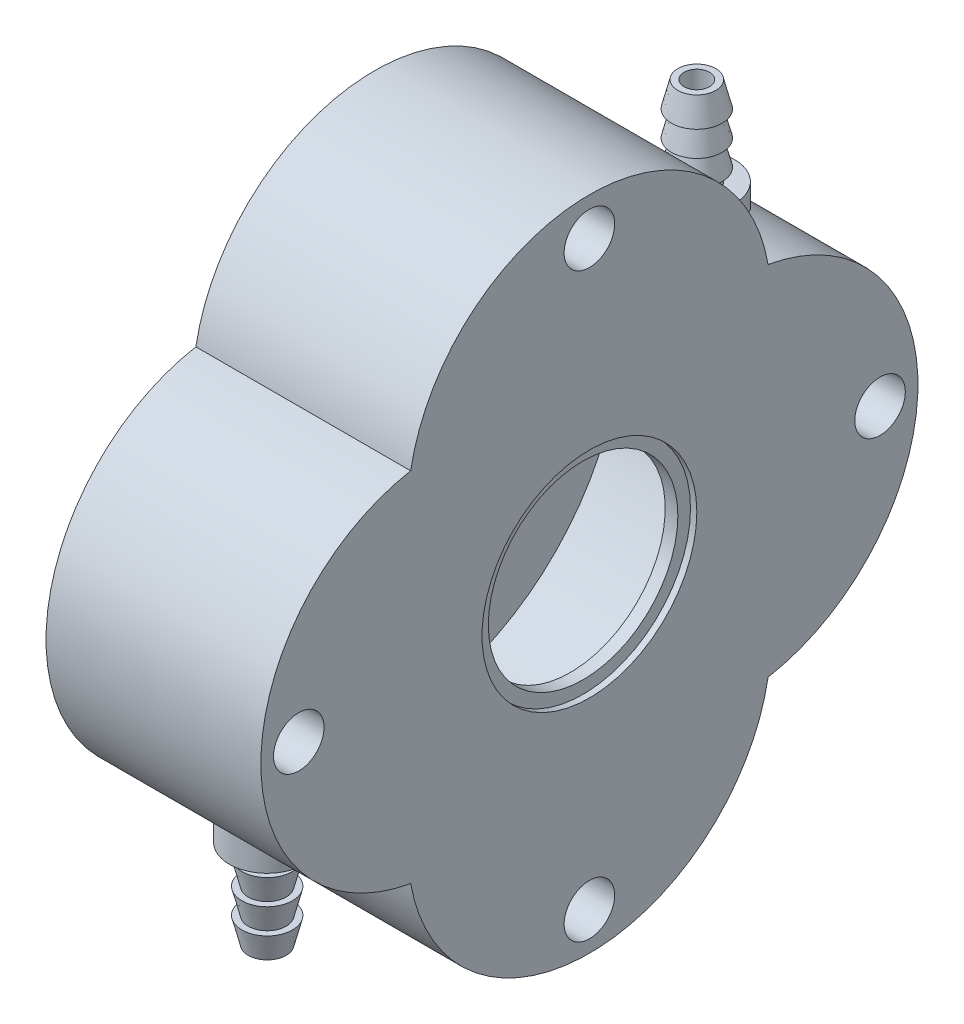
SolidWorks part; units mm, degrees
ref_plane "Front Plane" through (0, 0, 0) normal (0, 0, 1) x (1, 0, 0)
ref_plane "Top Plane" through (0, 0, 0) normal (0, 1, 0) x (1, 0, 0)
ref_plane "Right Plane" through (0, 0, 0) normal (1, 0, 0) x (0, 0, -1)
sketch "Sketch2" plane through (0, 0, 0) normal (1, 0, 0) x (0, 0, -1)
  line L1 (-14.1421, -14.1421) -> (14.1421, -14.1421) construction
  line L2 (-14.1421, -14.1421) -> (-14.1421, 14.1421) construction
  line L3 (-14.1421, 14.1421) -> (14.1421, 14.1421) construction
  line L4 (14.1421, -14.1421) -> (14.1421, 14.1421) construction
  circle A1 centre (0, 23) radius 2
  circle A2 centre (23, 0) radius 2
  circle A3 centre (0, -23) radius 2
  circle A4 centre (-23, 0) radius 2
  circle A5 centre (0, 0) radius 7.5
  circle A6 centre (0, 0) radius 8.5 construction
  circle A10 centre (0, 0) radius 18 construction
  circle A11 centre (0, 0) radius 26 construction
  circle A12 centre (0, -23) radius 3 construction
  circle A14 centre (23, 0) radius 3 construction
  arc A25 (-14.1421, 14.1421) -> (-14.1421, -14.1421) centre (-11.6378, 0) ccw
  arc A26 (-14.1421, -14.1421) -> (14.1421, -14.1421) centre (0, -11.6378) ccw
  circle A27 centre (0, 0) radius 20 construction
  arc A28 (14.1421, 14.1421) -> (-14.1421, 14.1421) centre (0, 11.6378) ccw
  arc A29 (14.1421, -14.1421) -> (14.1421, 14.1421) centre (11.6378, 0) ccw
  point P14 (0, 0)
  point P36 (0, 0)
  point P49 (0, 0)
  dimension "D1" = 36
  dimension "D3" = 4
  dimension "D5" = 15
  dimension "D6" = 17
  dimension "D7" = 52
  dimension "D8" = 40
  dimension "D4" = 23
  dimension "D2" = 4
  dimension "D9" = 4
extrude "Flange" add sketch "Sketch2" along normal mid plane 17
sketch "Sketch3" plane through (8.5, 0, 0) normal (1, 0, 0) x (0, 0, -1)
  circle A0 centre (0, 0) radius 8.5
  dimension "D1" = 17
extrude "O-Ring Seat" cut sketch "Sketch3" against normal blind 0.5
mirror "Mirror1" about plane through (0, 0, 0) normal (1, 0, 0) of "O-Ring Seat"
sketch "Sketch8" plane through (0, 0, 0) normal (-1, 0, 0) x (0, 0, 1)
  circle A0 centre (0, 0) radius 18
  dimension "D1" = 36
extrude "Cut-Extrude1" cut sketch "Sketch8" against normal mid plane 14
sketch "Sketch5" plane through (0, 0, 0) normal (0, 1, 0) x (1, 0, 0)
  line L1 (0, -28.6) -> (0, 28.6) construction
  circle A0 centre (0, 17) radius 1
  dimension "D1" = 2
  dimension "D2" = 17
extrude "Outlet" cut sketch "Sketch5" along normal through all
ref_plane "Plane2" through (0, 14.1421, 0) normal (0, 1, 0) x (1, 0, 0)
sketch "Sketch6" plane through (0, 14.1421, 0) normal (0, 1, 0) x (1, 0, 0)
  circle A2 centre (0, 17) radius 1
  circle A3 centre (0, 17) radius 3
  dimension "D1" = 2
extrude "Boss-Extrude2" add sketch "Sketch6" against normal up to next
ref_axis "Axis1" through (0, 14.1421, -17) along (0, -1, 0)
sketch "Sketch9" plane through (0, 0, 0) normal (1, 0, 0) x (0, 0, -1)
  line L0 (18, 14.1421) -> (18, 21.1421)
  line L1 (18, 21.1421) -> (18.5, 21.1421)
  line L2 (18.5, 21.1421) -> (19, 19.1421)
  line L3 (19, 19.1421) -> (18.5, 19.1421)
  line L4 (18.5, 19.1421) -> (19, 17.1421)
  line L5 (19, 17.1421) -> (18.5, 17.1421)
  line L6 (18.5, 17.1421) -> (19, 15.1421)
  line L7 (19, 15.1421) -> (18.5, 15.1421)
  line L8 (18.5, 15.1421) -> (18.5, 14.1421)
  line L9 (18.5, 14.1421) -> (18, 14.1421)
  line L10 (17, 14.1421) -> (17, -0.6906) construction
  line L11 (20, 14.1421) -> (14.1421, 14.1421) construction
  dimension "D1" = 0.5
  dimension "D2" = 0.5
  dimension "D3" = 2
  dimension "D4" = 1
  dimension "D5" = 1
revolve "Revolve1" add sketch "Sketch9" angle 360 about axis through (0, 14.1421, -17) along (0, -1, 0)
pattern_circular "Inlet" count 2 every 180 about axis through (8, 0, 0) along (1, 0, 0) of "Boss-Extrude2", "Revolve1", "Outlet"
